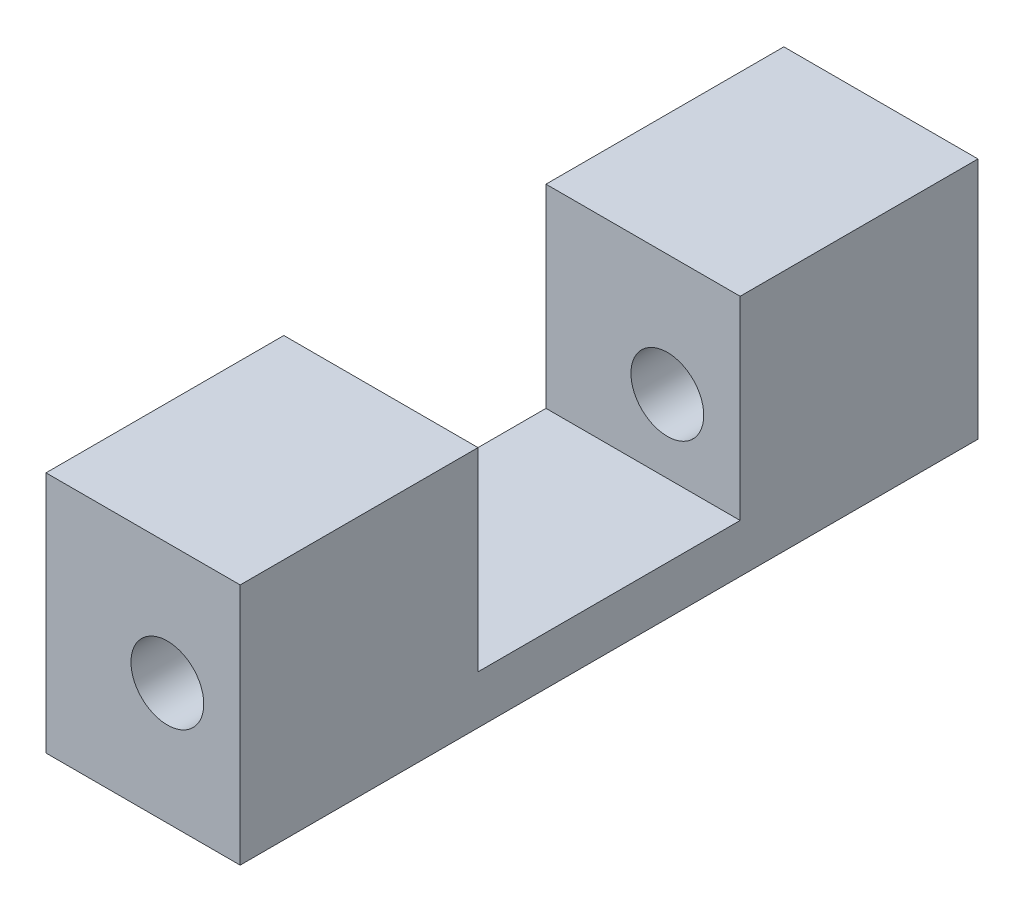
SolidWorks part; units mm, degrees
ref_plane "前视基准面" through (0, 0, 0) normal (0, 0, 1) x (1, 0, 0)
ref_plane "上视基准面" through (0, 0, 0) normal (0, 1, 0) x (1, 0, 0)
ref_plane "右视基准面" through (0, 0, 0) normal (1, 0, 0) x (0, 0, -1)
sketch "Sketch1" plane through (0, 0, 0) normal (0, 1, 0) x (1, 0, 0)
  line L1 (-2, -7.6) -> (2, -7.6)
  line L2 (-2, -7.6) -> (-2, 7.6)
  line L3 (-2, 7.6) -> (2, 7.6)
  line L4 (2, -7.6) -> (2, 7.6)
  line L5 (-2, -7.6) -> (2, 7.6) construction
  line L6 (-2, 7.6) -> (2, -7.6) construction
  point P0 (0, 0)
  dimension "D1" = 4
  dimension "D2" = 15.2
extrude "Boss-Extrude1" add sketch "Sketch1" along normal blind 1
sketch "Sketch2" plane through (0, 1, 0) normal (0, 1, 0) x (1, 0, 0)
  line L0 (2, -7.6) -> (2, 7.6) construction
  line L1 (-2, -7.6) -> (2, -7.6)
  line L2 (-2, -7.6) -> (-2, -2.7)
  line L3 (-2, -2.7) -> (2, -2.7)
  line L4 (2, -7.6) -> (2, -2.7)
  dimension "D1" = 2.7
extrude "Boss-Extrude2" add sketch "Sketch2" along normal blind 4
sketch "Sketch4" plane through (0, 0, 7.6) normal (0, 0, 1) x (1, 0, 0)
  line L0 (-2, 5) -> (2, 0) construction
  line L1 (0, 2.5) -> (0.5, 2.5) construction
  circle A0 centre (0.5, 2.5) radius 0.75
  dimension "D1" = 1.5
  dimension "D2" = 0.5
extrude "Cut-Extrude2" cut sketch "Sketch4" against normal up to next
mirror "Mirror3" about plane through (0, 0, 0) normal (0, 0, 1) of "Cut-Extrude2", "Boss-Extrude2"
